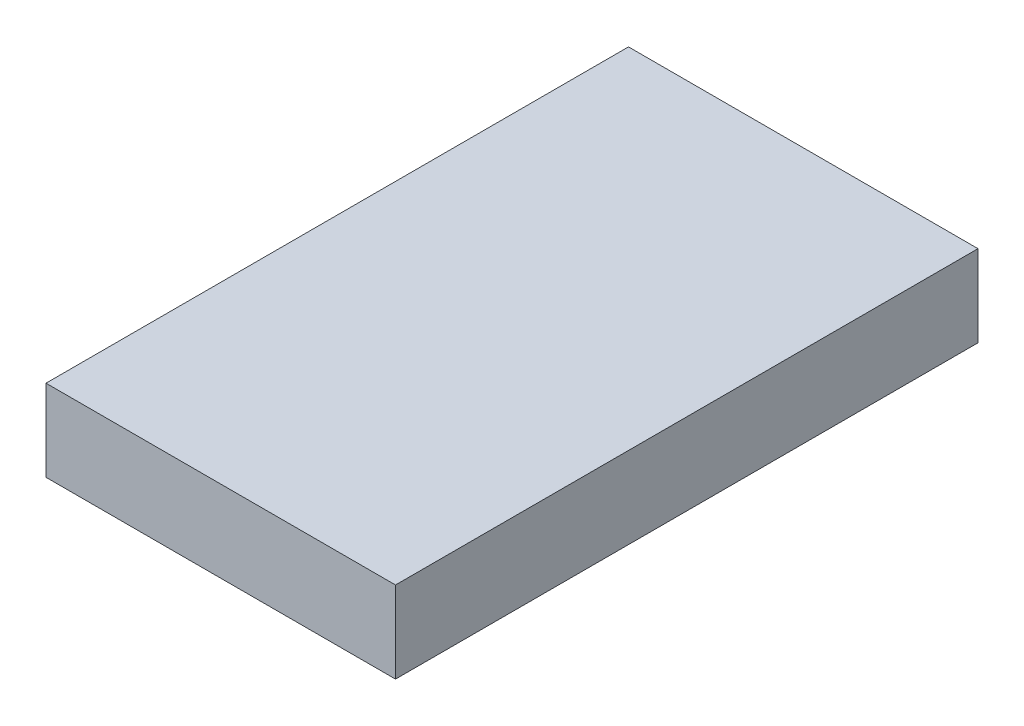
SolidWorks part; units mm, degrees
material "Glass"
ref_plane "Front Plane" through (0, 0, 0) normal (0, 0, 1) x (1, 0, 0)
ref_plane "Top Plane" through (0, 0, 0) normal (0, 1, 0) x (1, 0, 0)
ref_plane "Right Plane" through (0, 0, 0) normal (1, 0, 0) x (0, 0, -1)
sketch "Sketch1" plane through (0, 0, 0) normal (0, 1, 0) x (1, 0, 0)
  line L1 (-7.5, -12.5) -> (7.5, -12.5)
  line L2 (-7.5, -12.5) -> (-7.5, 12.5)
  line L3 (-7.5, 12.5) -> (7.5, 12.5)
  line L4 (7.5, -12.5) -> (7.5, 12.5)
  line L5 (-7.5, -12.5) -> (7.5, 12.5) construction
  line L6 (-7.5, 12.5) -> (7.5, -12.5) construction
  point P0 (0, 0)
  dimension "D1" = 15
  dimension "D2" = 25
extrude "Boss-Extrude1" add sketch "Sketch1" along normal mid plane 3.5
